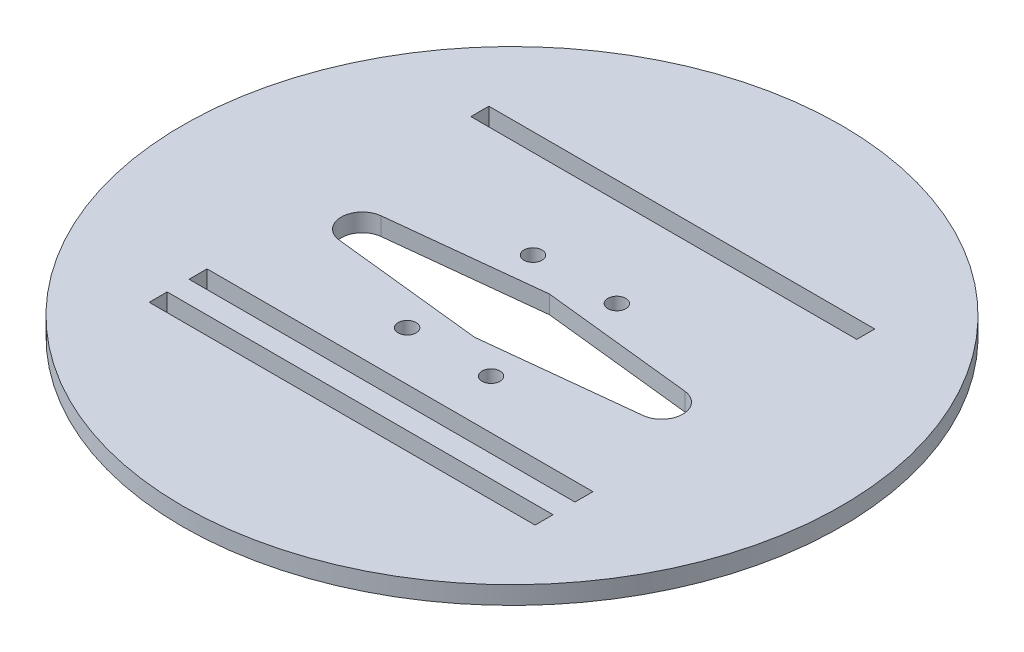
SolidWorks part; units mm, degrees
ref_plane "Front Plane" through (0, 0, 0) normal (0, 0, 1) x (1, 0, 0)
ref_plane "Top Plane" through (0, 0, 0) normal (0, 1, 0) x (1, 0, 0)
ref_plane "Right Plane" through (0, 0, 0) normal (1, 0, 0) x (0, 0, -1)
sketch "Sketch1" plane through (0, 0, 0) normal (0, 1, 0) x (1, 0, 0)
  circle A0 centre (0, 0) radius 55
  dimension "D1" = 110
extrude "Boss-Extrude1" add sketch "Sketch1" along normal blind 3 contours A0
sketch "Sketch3" plane through (0, 3, 0) normal (0, 1, 0) x (1, 0, 0)
  line L0 (-25.359, 3.5) -> (0, 6.25)
  line L1 (0, 6.25) -> (25.359, 3.5)
  line L2 (25.359, -3.5) -> (0, -6.25)
  line L3 (0, -6.25) -> (-25.359, -3.5)
  arc A0 (-25.359, 3.5) -> (-25.359, -3.5) centre (-24.9795, 0) ccw
  arc A1 (25.359, -3.5) -> (25.359, 3.5) centre (24.9795, 0) ccw
  point P8 (-28.5, 0)
  point P9 (28.5, 0)
  dimension "D1" = 57
  dimension "D2" = 12.5
  dimension "D3" = 7
  dimension "D4" = 6.25
  dimension "D5" = 28.5
extrude "Cut-Extrude1" cut sketch "Sketch3" against normal blind 3
sketch "Sketch4" plane through (0, 3, 0) normal (0, 1, 0) x (1, 0, 0)
  line L1 (32.2, -18.69) -> (-32.2, -18.69)
  line L2 (32.2, -18.69) -> (32.2, -21.69)
  line L3 (32.2, -21.69) -> (-32.2, -21.69)
  line L4 (-32.2, -18.69) -> (-32.2, -21.69)
  line L5 (-32.2, -25.35) -> (32.2, -25.35)
  line L6 (-32.2, -25.35) -> (-32.2, -28.35)
  line L7 (-32.2, -28.35) -> (32.2, -28.35)
  line L8 (32.2, -25.35) -> (32.2, -28.35)
  line L9 (-32.2, 25.34) -> (32.2, 25.34)
  line L10 (-32.2, 25.34) -> (-32.2, 28.34)
  line L11 (-32.2, 28.34) -> (32.2, 28.34)
  line L12 (32.2, 25.34) -> (32.2, 28.34)
  circle A0 centre (-7, -10.5) radius 1.5
  circle A1 centre (7, -10.5) radius 1.5
  circle A2 centre (-7, 10.5) radius 1.5
  circle A3 centre (7, 10.5) radius 1.5
  arc A4 (-25.359, 3.5) -> (-25.359, -3.5) centre (-24.9795, 0) ccw construction
  arc A5 (25.359, -3.5) -> (25.359, 3.5) centre (24.9795, 0) ccw construction
  point P22 (-7, -35.35)
  point P23 (0, 25.34)
  point P24 (0, -18.69)
  point P25 (-7, -40.6911)
  point P29 (-28.5, 0)
  point P33 (28.5, 0)
  dimension "D13" = 10.5
  dimension "D17" = 7
  dimension "D1" = 12.44
  dimension "D2" = 3.66
  dimension "D3" = 64.4
  dimension "D4" = 64.4
  dimension "D5" = 3
  dimension "D6" = 3
  dimension "D7" = 10.5
  dimension "D8" = 10.5
  dimension "D9" = 3
  dimension "D10" = 64.4
  dimension "D11" = 19.09
  dimension "D12" = 10.5
  dimension "D15" = 7
  dimension "D16" = 7
  dimension "D18" = 7
extrude "Cut-Extrude2" cut sketch "Sketch4" against normal blind 3
